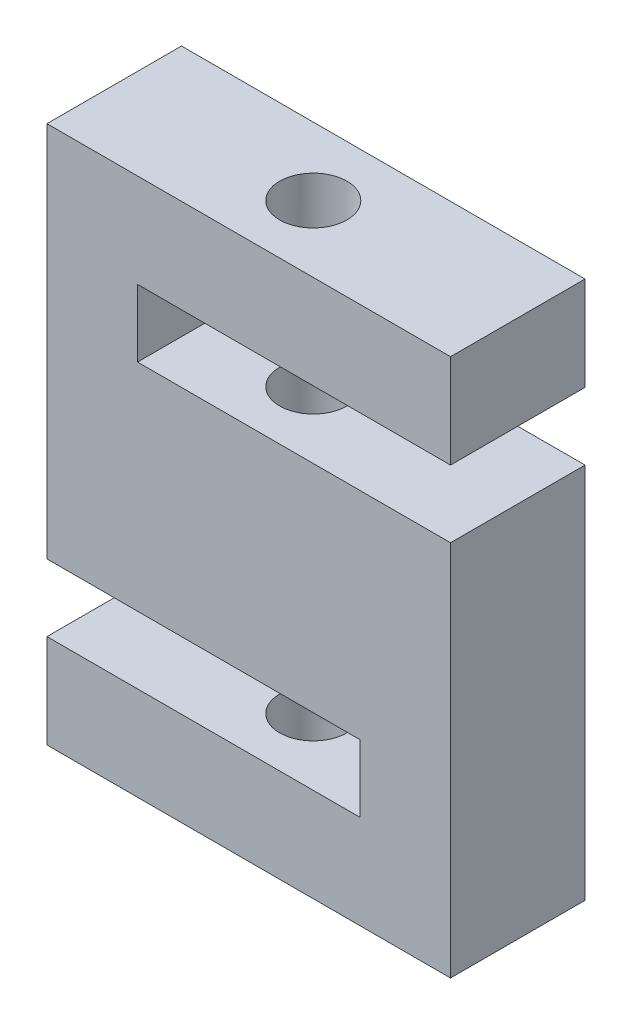
SolidWorks part; units mm, degrees
ref_plane "Front Plane" through (0, 0, 0) normal (0, 0, 1) x (1, 0, 0)
ref_plane "Top Plane" through (0, 0, 0) normal (0, 1, 0) x (1, 0, 0)
ref_plane "Right Plane" through (0, 0, 0) normal (1, 0, 0) x (0, 0, -1)
sketch "Sketch1" plane through (0, 0, 0) normal (0, 0, 1) x (1, 0, 0)
  line L0 (0, 80) -> (60, 80)
  line L1 (60, 80) -> (60, 66.0427)
  line L2 (60, 66.0427) -> (13.4703, 66.0427)
  line L3 (13.4703, 66.0427) -> (13.4703, 56.0427)
  line L4 (13.4703, 56.0427) -> (60, 56.0427)
  line L5 (60, 56.0427) -> (60, 0)
  line L6 (60, 0) -> (0, 0)
  line L7 (0, 0) -> (0, 13.9573)
  line L8 (0, 13.9573) -> (46.5297, 13.9573)
  line L9 (46.5297, 13.9573) -> (46.5297, 23.9573)
  line L10 (46.5297, 23.9573) -> (0, 23.9573)
  line L11 (0, 23.9573) -> (0, 80)
  dimension "D1" = 80
  dimension "D2" = 60
  dimension "D3" = 10
extrude "Boss-Extrude1" add sketch "Sketch1" along normal blind 20
sketch "Sketch2" plane through (0, 80, 0) normal (0, 1, 0) x (1, 0, 0)
  line L0 (0, -0.3994) -> (60, -20) construction
  line L1 (0, -20) -> (0, 0) construction
  line L2 (60, -20) -> (60, 0) construction
  line L3 (60, 0) -> (0, -20) construction
  circle A0 centre (29.6974, -10.1009) radius 5
  dimension "D1" = 10
extrude "Cut-Extrude1" cut sketch "Sketch2" against normal through all
